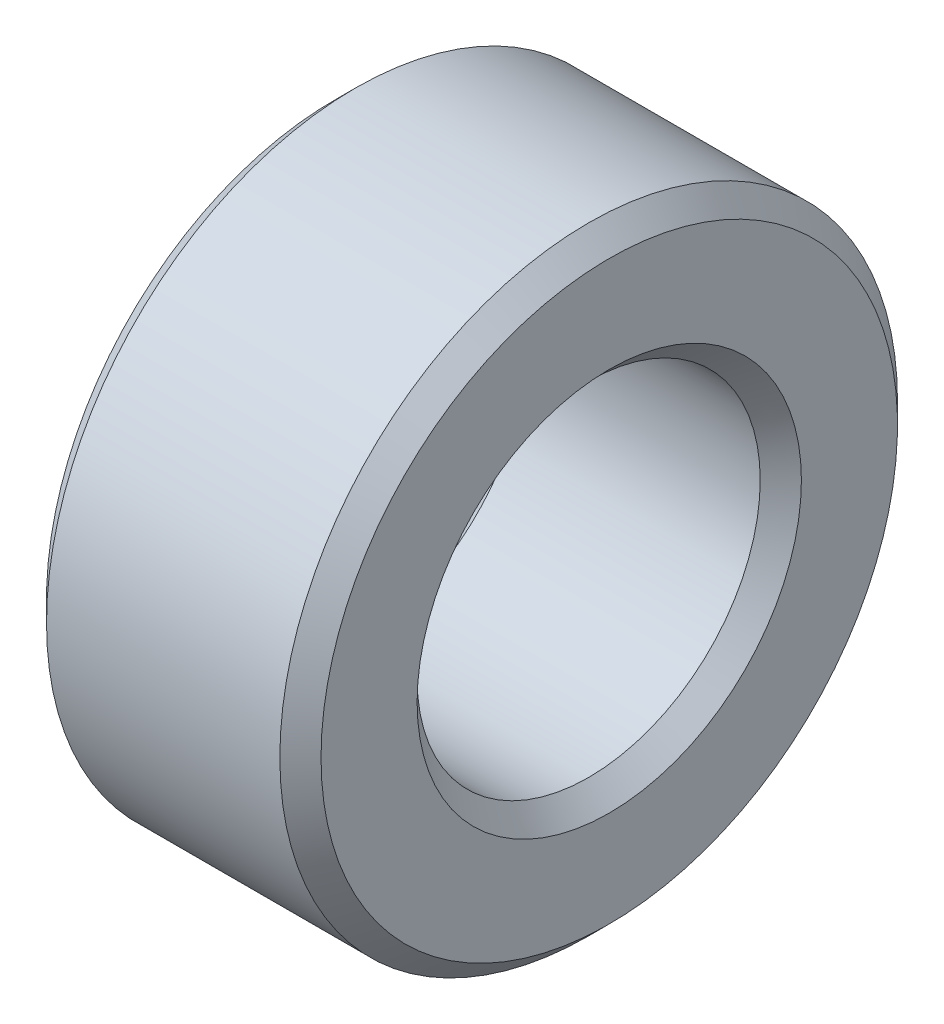
SolidWorks part; units mm, degrees
ref_plane "Přední rovina" through (0, 0, 0) normal (0, 0, 1) x (1, 0, 0)
ref_plane "Vrchní rovina" through (0, 0, 0) normal (0, 1, 0) x (1, 0, 0)
ref_plane "Pravá rovina" through (0, 0, 0) normal (1, 0, 0) x (0, 0, -1)
sketch "Skica1" plane through (0, 0, 0) normal (0, 0, 1) x (1, 0, 0)
  line L0 (0, 2.5) -> (4, 2.5)
  line L1 (4, 2.5) -> (4, 4.5)
  line L2 (4, 4.5) -> (0, 4.5)
  line L3 (0, 4.5) -> (0, 2.5)
  line L4 (0, 0) -> (4, 0) construction
  dimension "d_" = 5
  dimension "D" = 9
  dimension "L" = 4
revolve "Otočit kolem osy1" add sketch "Skica1" angle 360 about L4
chamfer "Zkosit1" distance 0.3 angle 45 4 edges at (0, 0, 4.5) (4, 0, 4.5) (4, 0, 2.5) (0, 0, 2.5)
